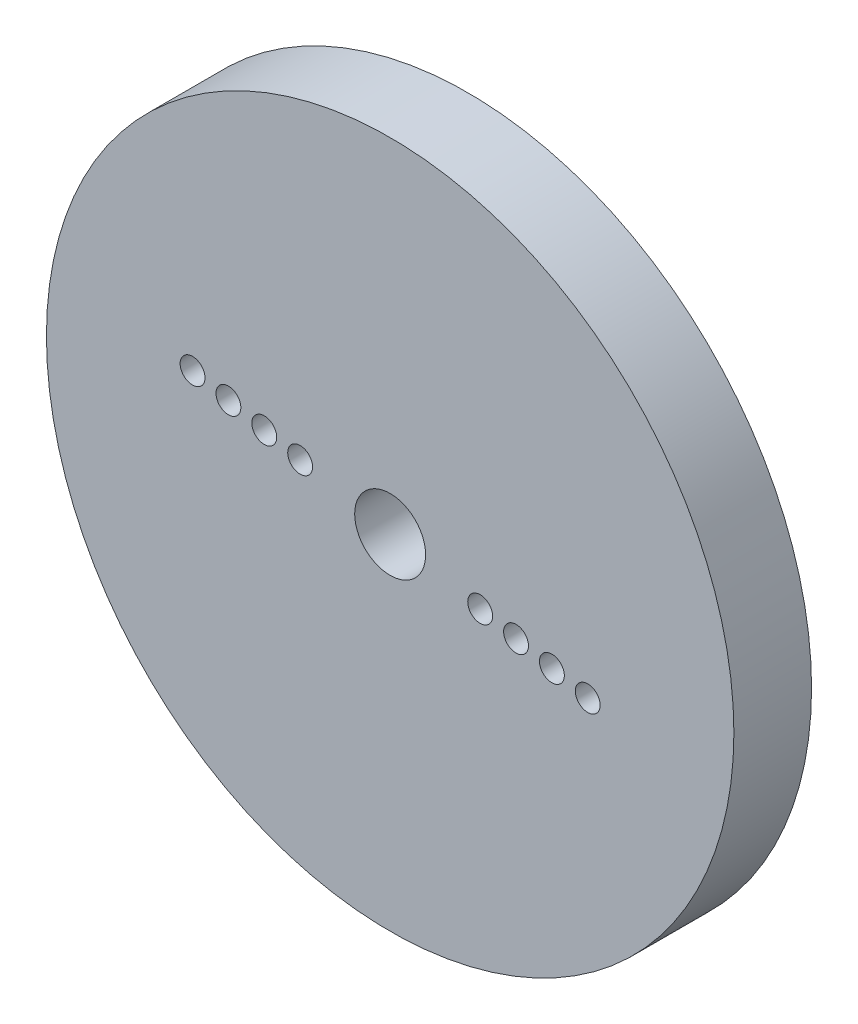
SolidWorks part; units mm, degrees
ref_plane "Front Plane" through (0, 0, 0) normal (0, 0, 1) x (1, 0, 0)
ref_plane "Top Plane" through (0, 0, 0) normal (0, 1, 0) x (1, 0, 0)
ref_plane "Right Plane" through (0, 0, 0) normal (1, 0, 0) x (0, 0, -1)
sketch "Sketch1" plane through (0, 0, 0) normal (0, 0, 1) x (1, 0, 0)
  circle A0 centre (0, 0) radius 28.098
  dimension "D1" = 56.196
extrude "Boss-Extrude1" add sketch "Sketch1" along normal blind 6.35 contours A0
sketch "Sketch2" plane through (0, 0, 0) normal (0, 0, -1) x (-1, 0, 0)
  circle A0 centre (-13.2207, -2.8764) radius 1.016
  circle A1 centre (-16.1521, -3.5142) radius 1.016
  circle A2 centre (-10.2893, -2.2386) radius 1.016
  circle A3 centre (-7.3579, -1.6008) radius 1.016
  circle A4 centre (7.3579, 1.6008) radius 1.016
  circle A5 centre (10.2893, 2.2386) radius 1.016
  circle A6 centre (13.2207, 2.8764) radius 1.016
  circle A7 centre (16.1521, 3.5142) radius 1.016
  circle A9 centre (0, 0) radius 2.9
  dimension "D1" = 2.032
  dimension "D2" = 2.032
  dimension "D3" = 2.032
  dimension "D4" = 2.032
  dimension "D5" = 2.032
  dimension "D6" = 2.032
  dimension "D7" = 2.032
  dimension "D8" = 2.032
extrude "Cut-Extrude1" cut sketch "Sketch2" against normal up to surface (6.35 mm away) up to face at (28.098, 0, 6.35)
